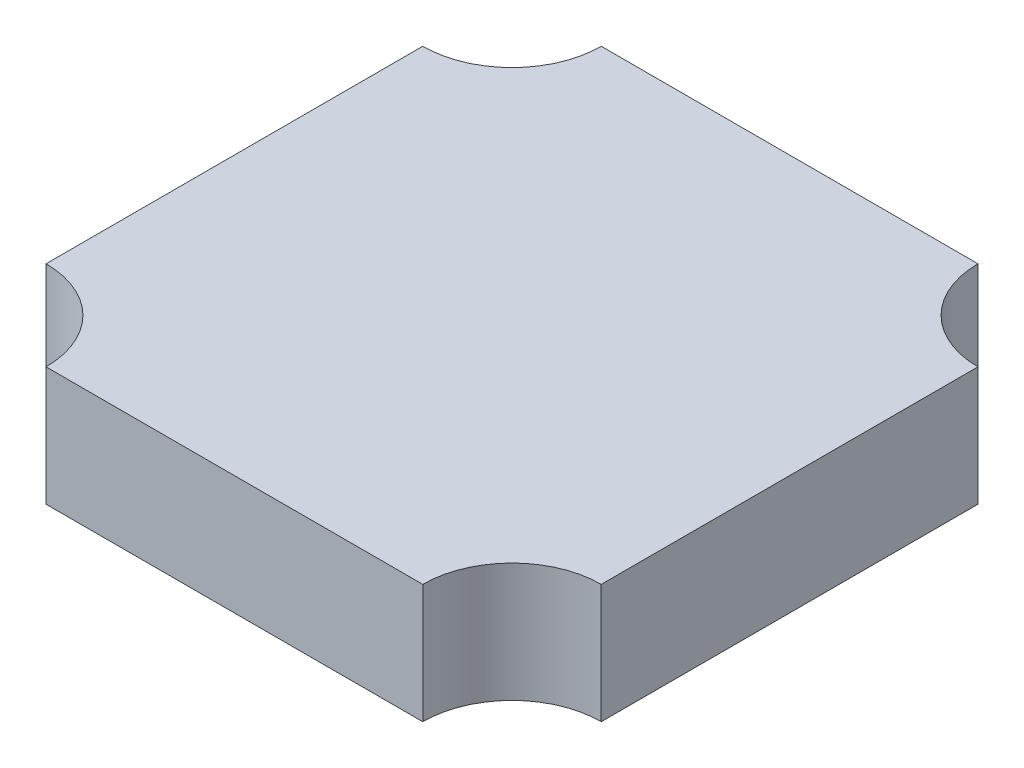
SolidWorks part; units mm, degrees
material "1060 Alloy"
ref_plane "Front Plane" through (0, 0, 0) normal (0, 0, 1) x (1, 0, 0)
ref_plane "Top Plane" through (0, 0, 0) normal (0, 1, 0) x (1, 0, 0)
ref_plane "Right Plane" through (0, 0, 0) normal (1, 0, 0) x (0, 0, -1)
sketch "Sketch1" plane through (0, 0, 0) normal (0, 1, 0) x (1, 0, 0)
  line L1 (-19, 28) -> (19, 28)
  line L2 (-28, 19) -> (-28, -19)
  line L3 (-19, -28) -> (19, -28)
  line L4 (28, 19) -> (28, -19)
  line L5 (-21.636, 21.636) -> (21.636, -21.636) construction
  line L6 (-21.636, -21.636) -> (21.636, 21.636) construction
  arc A0 (28, -19) -> (19, -28) centre (28, -28) ccw
  arc A1 (19, 28) -> (28, 19) centre (28, 28) ccw
  arc A2 (-28, 19) -> (-19, 28) centre (-28, 28) ccw
  arc A3 (-19, -28) -> (-28, -19) centre (-28, -28) ccw
  point P0 (0, 0)
  dimension "D3" = 18
  dimension "D1" = 56
  dimension "D2" = 56
extrude "Boss-Extrude1" add sketch "Sketch1" along normal blind 12
